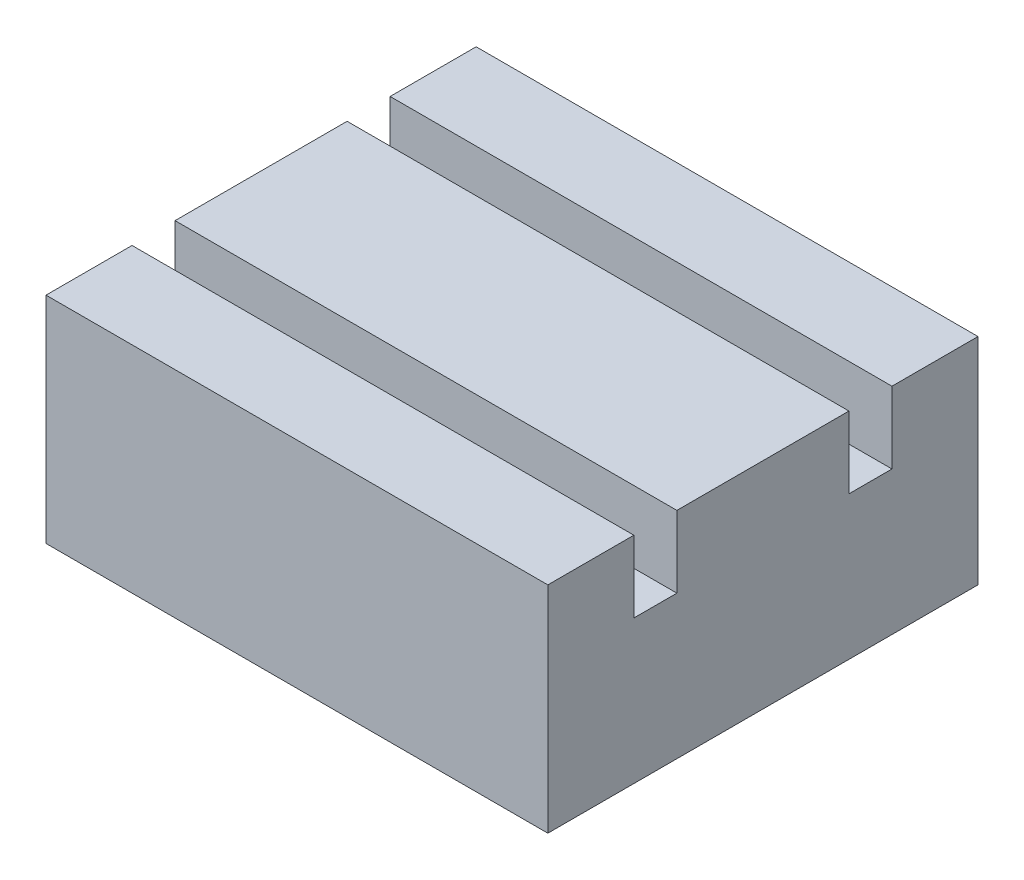
SolidWorks part; units mm, degrees
ref_plane "Front Plane" through (0, 0, 0) normal (0, 0, 1) x (1, 0, 0)
ref_plane "Top Plane" through (0, 0, 0) normal (0, 1, 0) x (1, 0, 0)
ref_plane "Right Plane" through (0, 0, 0) normal (1, 0, 0) x (0, 0, -1)
sketch "Sketch3" plane through (0, 0, 0) normal (0, 1, 0) x (1, 0, 0)
  line L1 (35, -30) -> (-35, -30)
  line L2 (35, -30) -> (35, 30)
  line L3 (35, 30) -> (-35, 30)
  line L4 (-35, -30) -> (-35, 30)
  line L5 (35, -30) -> (-35, 30) construction
  line L6 (35, 30) -> (-35, -30) construction
  point P0 (0, 0)
  dimension "D1" = 70
  dimension "D2" = 60
extrude "Boss-Extrude1" add sketch "Sketch3" against normal blind 30
sketch "Sketch4" plane through (35, 0, 0) normal (1, 0, 0) x (0, 0, -1)
  line L0 (-30, 0) -> (-15, 0) construction
  line L1 (-30, 0) -> (30, 0) construction
  line L3 (-18, 10) -> (-12, 10)
  line L4 (-18, 10) -> (-18, -10)
  line L5 (-18, -10) -> (-12, -10)
  line L6 (-12, 10) -> (-12, -10)
  line L7 (-18, 10) -> (-12, -10) construction
  line L8 (-18, -10) -> (-12, 10) construction
  dimension "D1" = 15
  dimension "D2" = 6
  dimension "D3" = 20
extrude "Cut-Extrude1" cut sketch "Sketch4" against normal through all
mirror "Mirror1" about plane through (0, 0, 0) normal (0, 0, 1) of "Cut-Extrude1"
